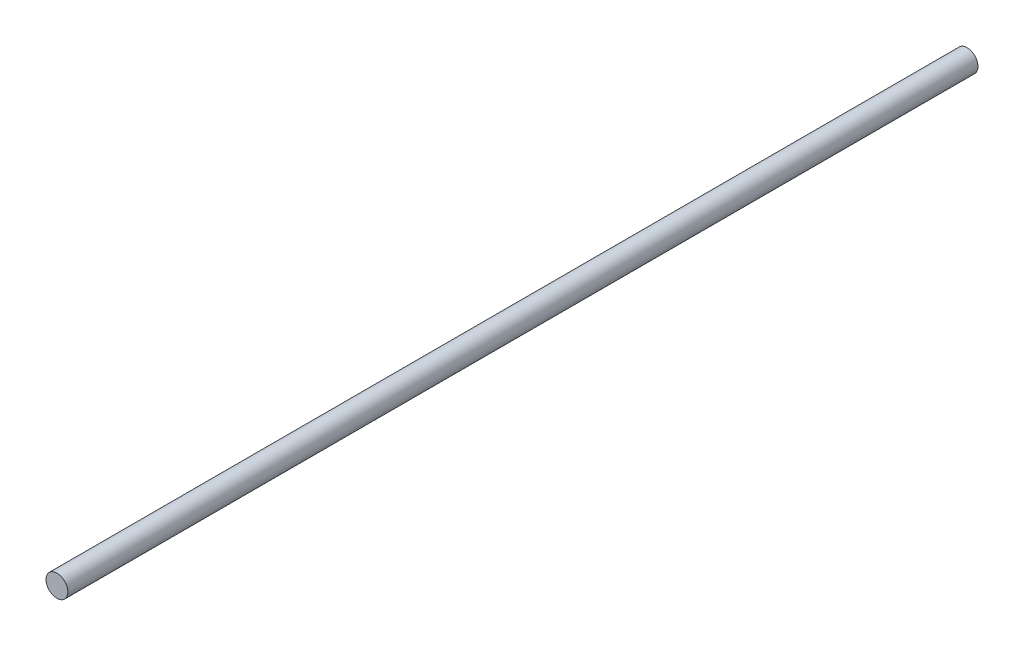
SolidWorks part; units mm, degrees
ref_plane "Front Plane" through (0, 0, 0) normal (0, 0, 1) x (1, 0, 0)
ref_plane "Top Plane" through (0, 0, 0) normal (0, 1, 0) x (1, 0, 0)
ref_plane "Right Plane" through (0, 0, 0) normal (1, 0, 0) x (0, 0, -1)
sketch "Sketch1" plane through (0, 0, 0) normal (0, 0, 1) x (1, 0, 0)
  circle A0 centre (0, 0) radius 4.2
extrude "Boss-Extrude1" add sketch "Sketch1" along normal mid plane 350
